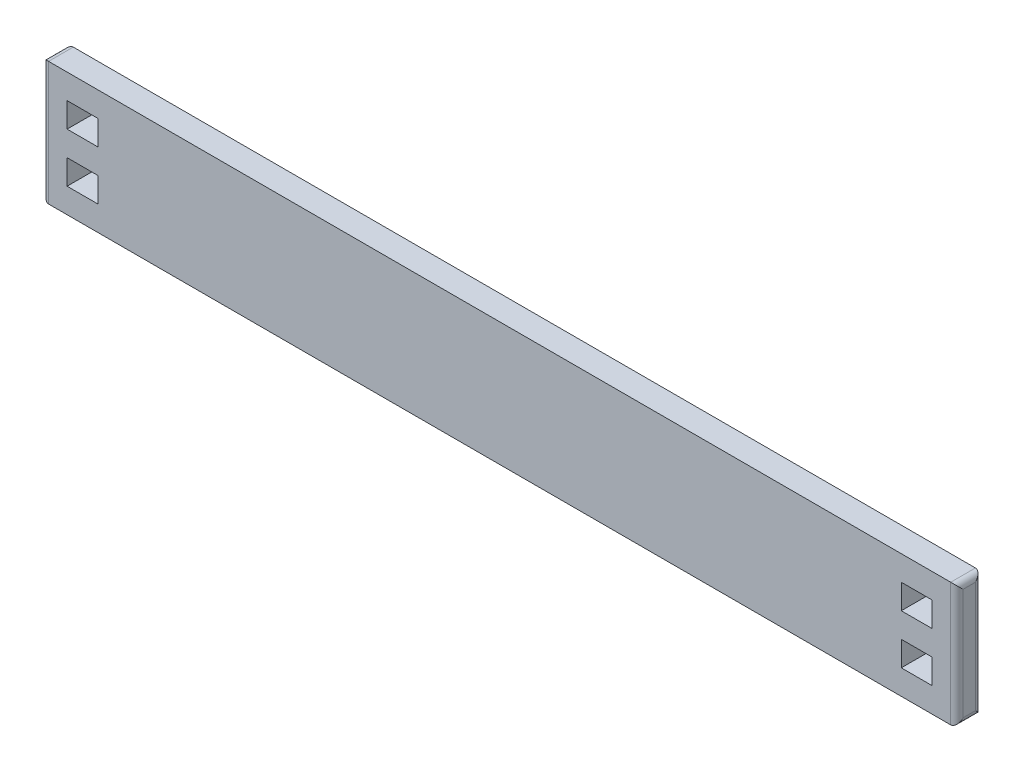
SolidWorks part; units mm, degrees
ref_plane "前视基准面" through (0, 0, 0) normal (0, 0, 1) x (1, 0, 0)
ref_plane "上视基准面" through (0, 0, 0) normal (0, 1, 0) x (1, 0, 0)
ref_plane "右视基准面" through (0, 0, 0) normal (1, 0, 0) x (0, 0, -1)
other "Configuration Table"
sketch "草图1" plane through (0, 0, 0) normal (0, 0, 1) x (1, 0, 0)
  line L0 (0, -10) -> (0, 10)
  line L1 (-74, -10) -> (74, -10)
  line L2 (-74, -10) -> (-74, 10)
  line L3 (-74, 10) -> (74, 10)
  line L4 (74, -10) -> (74, 10)
  line L5 (-74, -10) -> (74, 10) construction
  line L6 (-74, 10) -> (74, -10) construction
  point P0 (0, 0)
  dimension "D1" = 20
  dimension "138" = 148
extrude "凸台-拉伸1" add sketch "草图1" along normal blind 4 contours L3 L2 L1 L0 | L1 L4 L3 L0
sketch "草图2" plane through (0, 0, 4) normal (0, 0, 1) x (1, 0, 0)
  line L0 (-74, -10) -> (-74, 10) construction
  line L1 (-70, 6) -> (-65, 6)
  line L2 (-70, 6) -> (-70, 2)
  line L3 (-70, 2) -> (-65, 2)
  line L4 (-65, 6) -> (-65, 2)
  line L5 (-70, 6) -> (-65, 2) construction
  line L6 (-70, 2) -> (-65, 6) construction
  line L7 (-74, 10) -> (74, 10) construction
  line L9 (-74, 0) -> (74, 0)
  line L10 (74, -10) -> (74, 10) construction
  line L11 (0, -10) -> (0, 10)
  line L12 (-74, -10) -> (74, -10) construction
  line L13 (-70, -2) -> (-65, -2)
  line L14 (-65, -6) -> (-65, -2)
  line L15 (-70, -6) -> (-65, -6)
  line L16 (-70, -6) -> (-70, -2)
  line L17 (70, 2) -> (65, 2)
  line L18 (65, 6) -> (65, 2)
  line L19 (70, 6) -> (65, 6)
  line L20 (70, 6) -> (70, 2)
  line L21 (70, -6) -> (70, -2)
  line L22 (70, -6) -> (65, -6)
  line L23 (65, -6) -> (65, -2)
  line L24 (70, -2) -> (65, -2)
  point P0 (-67.5, 4)
  dimension "D1" = 4
  dimension "D2" = 4
  dimension "D3" = 4
  dimension "D4" = 5
extrude "切除-拉伸1" cut sketch "草图2" against normal blind 5 contours L16 L15 L14 L13 | L4 L1 L2 L3 | L20 L19 L18 L17 | L21 L24 L23 L22
fillet "圆角1" radius 1 8 edges at (74, -10, 2) (74, 0, 0) (74, 0, 4) (74, 10, 2) (-74, 10, 2) (-74, 0, 0) (-74, 0, 4) (-74, -10, 2)
